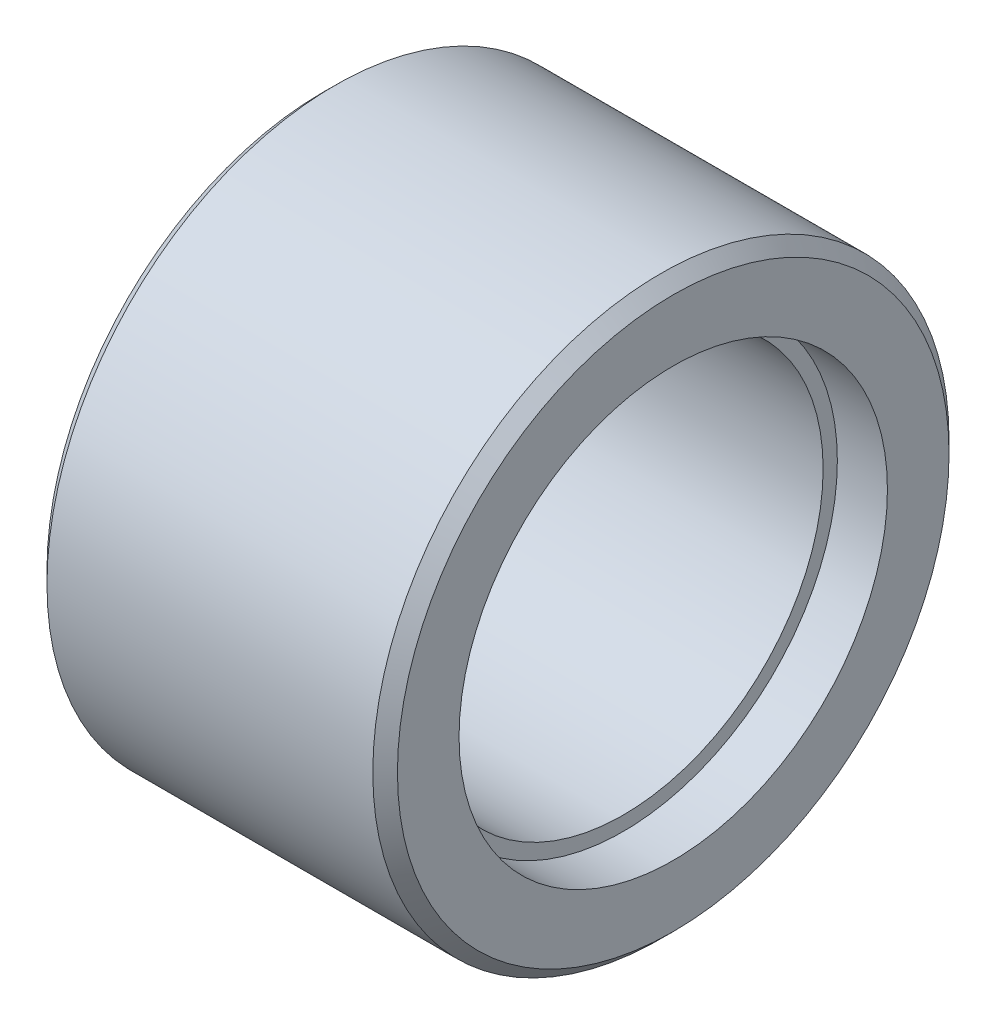
SolidWorks part; units mm, degrees
material "Rubber"
ref_plane "Front Plane" through (0, 0, 0) normal (0, 0, 1) x (1, 0, 0)
ref_plane "Top Plane" through (0, 0, 0) normal (0, 1, 0) x (1, 0, 0)
ref_plane "Right Plane" through (0, 0, 0) normal (1, 0, 0) x (0, 0, -1)
sketch "Sketch1" plane through (0, 0, 0) normal (0, 0, 1) x (1, 0, 0)
  line L0 (0, 0) -> (-92.7637, 0) construction
  line L1 (-75.8997, 8.6931) -> (-73.8677, 8.6931)
  line L2 (-73.8677, 8.6931) -> (-73.8677, 8.1153)
  line L3 (-73.8677, 8.1153) -> (-63.7077, 8.1153)
  line L4 (-63.7077, 8.1153) -> (-63.7077, 8.6931)
  line L5 (-63.7077, 8.6931) -> (-61.6757, 8.6931)
  line L6 (-61.6757, 8.6931) -> (-61.6757, 11.1931)
  line L7 (-62.1757, 11.6931) -> (-75.3997, 11.6931)
  line L8 (-75.8997, 11.1931) -> (-75.8997, 8.6931)
  line L9 (-75.3997, 11.6931) -> (-75.8997, 11.1931)
  line L10 (-61.6757, 11.1931) -> (-62.1757, 11.6931)
  point P10 (-61.6757, 11.6931)
  point P11 (-75.8997, 11.6931)
  dimension "D1" = 16.2306
  dimension "D2" = 17.3863
  dimension "D3" = 17.3863
  dimension "D4" = 10.16
  dimension "D5" = 2.032
  dimension "D6" = 14.224
  dimension "D7" = 3
revolve "Revolve1" add sketch "Sketch1" angle 360 about L0
